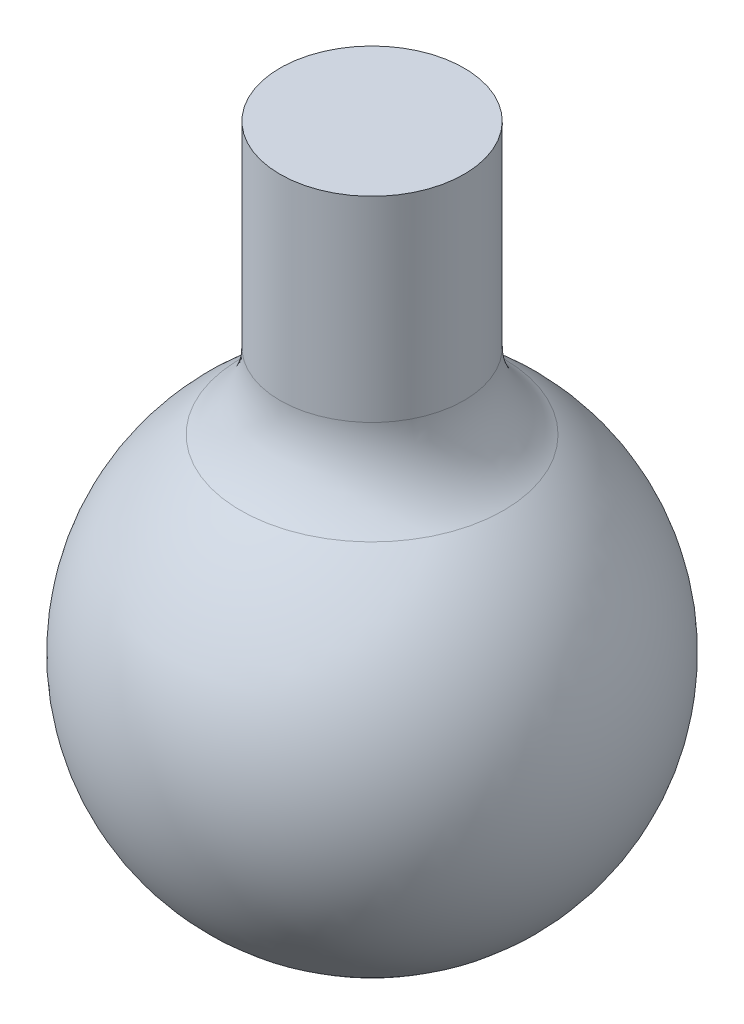
SolidWorks part; units mm, degrees
material "Alumina"
ref_plane "Front Plane" through (0, 0, 0) normal (0, 0, 1) x (1, 0, 0)
ref_plane "Top Plane" through (0, 0, 0) normal (0, 1, 0) x (1, 0, 0)
ref_plane "Right Plane" through (0, 0, 0) normal (1, 0, 0) x (0, 0, -1)
sketch "Sketch1" plane through (0, 0, 0) normal (0, 0, 1) x (1, 0, 0)
  line L0 (0, 5) -> (0, -5)
  arc A0 (0, 5) -> (0, -5) centre (0, 0) ccw
  dimension "D1" = 10
revolve "Revolve1" add sketch "Sketch1" angle 360 about L0
ref_plane "Plane1" through (0, 10, 0) normal (0, 1, 0) x (1, 0, 0)
sketch "Sketch2" plane through (0, 10, 0) normal (0, 1, 0) x (1, 0, 0)
  circle A0 centre (0, 0) radius 2
  dimension "D1" = 4
extrude "Boss-Extrude2" add sketch "Sketch2" against normal up to surface (5.4174 mm away)
fillet "Fillet1" radius 2 1 edges at (0, 4.5826, -2)
